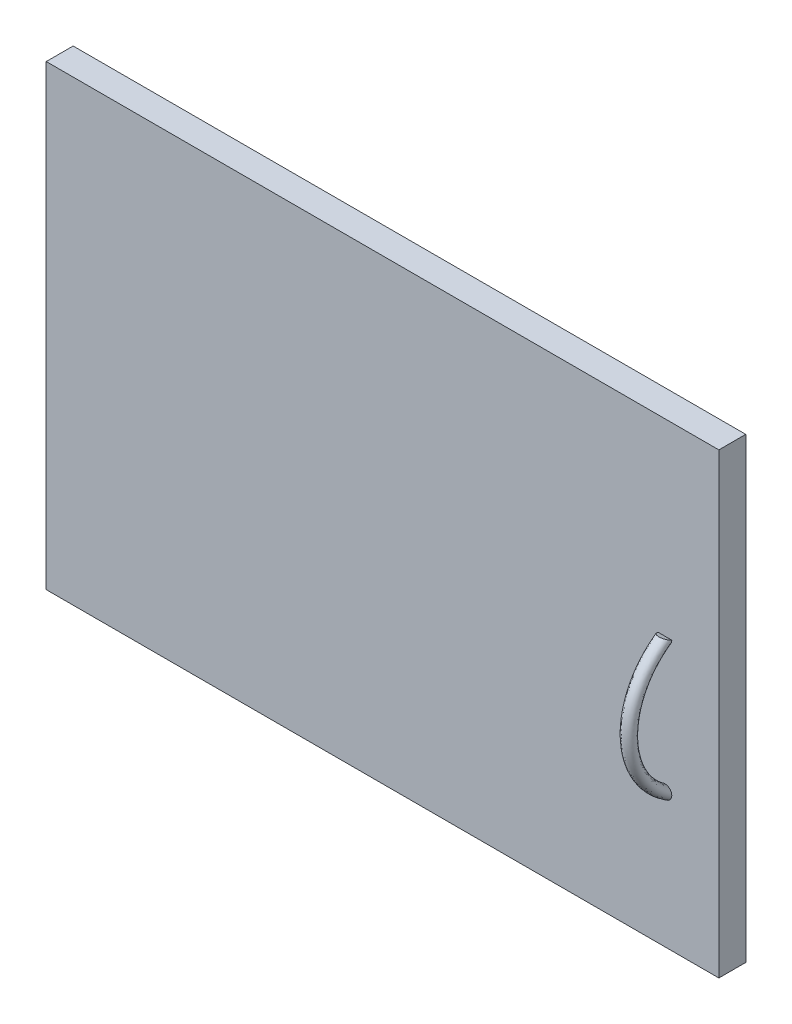
SolidWorks part; units mm, degrees
ref_plane "前基準面" through (0, 0, 0) normal (0, 0, 1) x (1, 0, 0)
ref_plane "上基準面" through (0, 0, 0) normal (0, 1, 0) x (1, 0, 0)
ref_plane "右基準面" through (0, 0, 0) normal (1, 0, 0) x (0, 0, -1)
sketch "草圖1" plane through (0, 0, 0) normal (0, 0, 1) x (1, 0, 0)
  line L1 (-12.5, 8.5) -> (12.5, 8.5)
  line L2 (-12.5, 8.5) -> (-12.5, -8.5)
  line L3 (-12.5, -8.5) -> (12.5, -8.5)
  line L4 (12.5, 8.5) -> (12.5, -8.5)
  line L5 (-12.5, 8.5) -> (12.5, -8.5) construction
  line L6 (-12.5, -8.5) -> (12.5, 8.5) construction
  point P0 (0, 0)
  dimension "D1" = 25
  dimension "D2" = 17
extrude "填料-伸長1" add sketch "草圖1" along normal blind 1
ref_plane "平面1" through (10.5, 0, 0) normal (1, 0, 0) x (0, 0, -1)
sketch "草圖3" plane through (0, 0, 1) normal (0, 0, 1) x (1, 0, 0)
  line L0 (10.5, 8.5) -> (10.5, -8.5) construction
  line L1 (12.5, 8.5) -> (-12.5, 8.5) construction
  line L2 (-12.5, -8.5) -> (12.5, -8.5) construction
  line L3 (12.5, -8.5) -> (12.5, 8.5) construction
  circle A0 centre (10.5, -3.5) radius 0.25
  dimension "D2" = 0.5
  dimension "D1" = 2
  dimension "D3" = 5
sketch "草圖4" plane through (10.5, 0, 0) normal (1, 0, 0) x (0, 0, -1)
  line L0 (-1, 8.5) -> (-1, -8.5) construction
  arc A0 (-1, -3.5) -> (-1, 1.5) centre (0.6583, -1) cw
  point P4 (1.1734, -1.432)
  dimension "D1" = 3
  dimension "D2" = 5
sweep "掃出1" add profiles "草圖3" path "草圖4"
